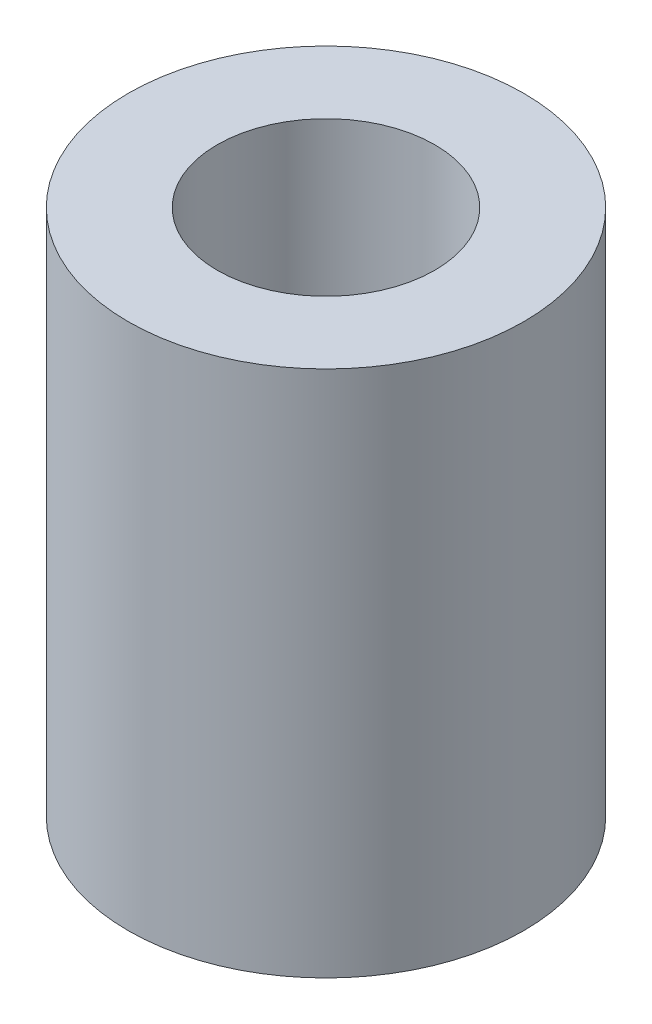
SolidWorks part; units mm, degrees
ref_plane "前视基准面" through (0, 0, 0) normal (0, 0, 1) x (1, 0, 0)
ref_plane "上视基准面" through (0, 0, 0) normal (0, 1, 0) x (1, 0, 0)
ref_plane "右视基准面" through (0, 0, 0) normal (1, 0, 0) x (0, 0, -1)
sketch "草图1" plane through (0, 0, 0) normal (0, 1, 0) x (1, 0, 0)
  circle A0 centre (0, 0) radius 1.65
  circle A1 centre (0, 0) radius 3
  dimension "D1" = 3.3
  dimension "D2" = 6
extrude "凸台-拉伸1" add sketch "草图1" along normal blind 8
